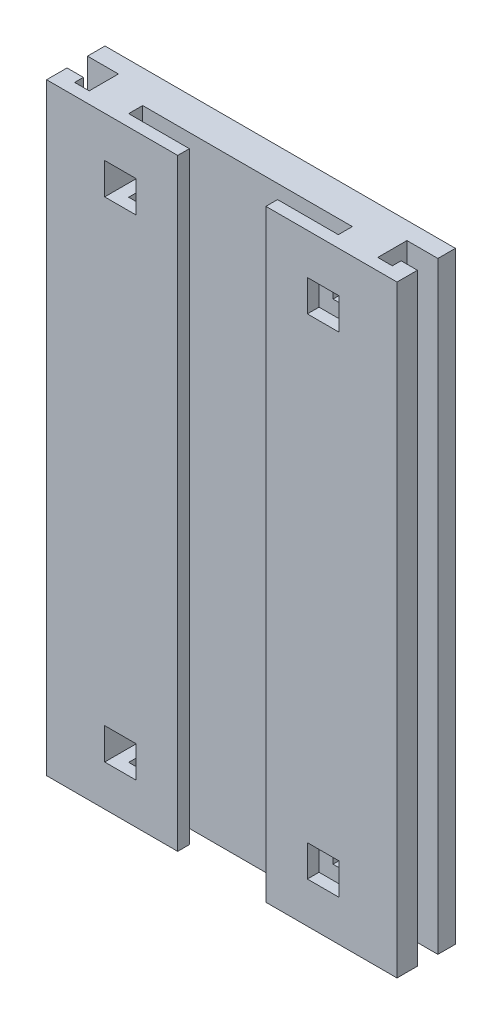
SolidWorks part; units mm, degrees
ref_plane "Front Plane" through (0, 0, 0) normal (1, 0, 0) x (0, 1, 0)
ref_plane "Top Plane" through (0, 0, 0) normal (0, 0, 1) x (0, 1, 0)
ref_plane "Right Plane" through (0, 0, 0) normal (0, 1, 0) x (-1, 0, 0)
sketch "Sketch1" plane through (0, 0, 0) normal (0, 0, 1) x (0, 1, 0)
  line L1 (-51.6, -30) -> (51.6, -30)
  line L2 (-51.6, -30) -> (-51.6, 30)
  line L3 (-51.6, 30) -> (51.6, 30)
  line L4 (51.6, -30) -> (51.6, 30)
  line L5 (-51.6, -30) -> (51.6, 30) construction
  line L6 (-51.6, 30) -> (51.6, -30) construction
  point P0 (0, 0)
  dimension "D1" = 103.2
  dimension "D2" = 60
extrude "Boss-Extrude1" add sketch "Sketch1" along normal blind 10
sketch "Sketch14" plane through (0, 51.6, 0) normal (0, 1, 0) x (-1, 0, 0)
  line L0 (-30, 10) -> (-30, 0) construction
  line L1 (-30, 6.5) -> (-27.2, 6.5)
  line L2 (-30, 6.5) -> (-30, 3)
  line L3 (-30, 3) -> (-24.7, 3)
  line L4 (-24.7, 6) -> (-24.7, 3)
  line L5 (-30, 10) -> (30, 10) construction
  line L7 (-27.2, 6.5) -> (-27.2, 8)
  line L8 (-27.2, 8) -> (-24.7, 8)
  line L9 (-24.7, 6) -> (-24.7, 8)
  line L17 (0, 10) -> (0, 0) construction
  line L18 (30, 6.5) -> (30, 3)
  line L19 (30, 3) -> (24.7, 3)
  line L20 (24.7, 6) -> (24.7, 3)
  line L21 (24.7, 6) -> (24.7, 8)
  line L22 (27.2, 8) -> (24.7, 8)
  line L23 (27.2, 6.5) -> (27.2, 8)
  line L24 (30, 6.5) -> (27.2, 6.5)
  line L25 (17.95, 8) -> (7.55, 8)
  line L26 (-17.95, 8) -> (-17.95, 5.6)
  line L27 (17.95, 8) -> (17.95, 5.6)
  line L28 (17.95, 5.6) -> (-17.95, 5.6)
  line L29 (-7.55, 8) -> (-7.55, 10)
  line L30 (-7.55, 10) -> (7.55, 10)
  line L31 (7.55, 10) -> (7.55, 8)
  line L32 (-7.55, 8) -> (-17.95, 8)
  point P24 (0, 8)
  dimension "D1" = 3.5
  dimension "D2" = 3.5
  dimension "D3" = 2
  dimension "D4" = 1.5
  dimension "D5" = 5.3
  dimension "D6" = 2.5
  dimension "D7" = 10.4
  dimension "D8" = 2.4
  dimension "D9" = 15.1
  dimension "D10" = 10.4
  dimension "D11" = 2.8
extrude "Cut-Extrude6" cut sketch "Sketch14" against normal through all
sketch "Sketch16" plane through (0, 0, 10) normal (0, 0, 1) x (1, 0, 0)
  line L0 (0, -0.9301) -> (0, 50.2361) construction
  line L1 (0, -0.9301) -> (0, -51.6) construction
  line L2 (17.95, -51.6) -> (-17.95, -51.6) construction
  line L3 (17.35, -39.2) -> (17.35, -44.6) construction
  line L4 (7.55, -51.6) -> (30, -51.6) construction
  line L5 (7.55, -51.6) -> (7.55, 51.6) construction
  line L6 (14.65, -39.2) -> (20.05, -39.2)
  line L7 (14.65, -39.2) -> (14.65, -44.6)
  line L8 (14.65, -44.6) -> (20.05, -44.6)
  line L9 (20.05, -39.2) -> (20.05, -44.6)
  line L11 (30, 0) -> (-30, 0) construction
  line L12 (30, -51.6) -> (30, 51.6) construction
  line L13 (-30, 51.6) -> (-30, -51.6) construction
  line L14 (20.05, 39.2) -> (20.05, 44.6)
  line L15 (14.65, 44.6) -> (20.05, 44.6)
  line L16 (14.65, 39.2) -> (14.65, 44.6)
  line L17 (14.65, 39.2) -> (20.05, 39.2)
  line L18 (-14.65, 39.2) -> (-20.05, 39.2)
  line L19 (-14.65, 39.2) -> (-14.65, 44.6)
  line L20 (-14.65, 44.6) -> (-20.05, 44.6)
  line L21 (-20.05, 39.2) -> (-20.05, 44.6)
  line L22 (-20.05, -39.2) -> (-20.05, -44.6)
  line L23 (-14.65, -44.6) -> (-20.05, -44.6)
  line L24 (-14.65, -39.2) -> (-14.65, -44.6)
  line L25 (-14.65, -39.2) -> (-20.05, -39.2)
  dimension "D2" = 5.4
  dimension "D3" = 5.4
  dimension "D4" = 7.1
  dimension "D5" = 7
extrude "Cut-Extrude7" cut sketch "Sketch16" against normal through all
